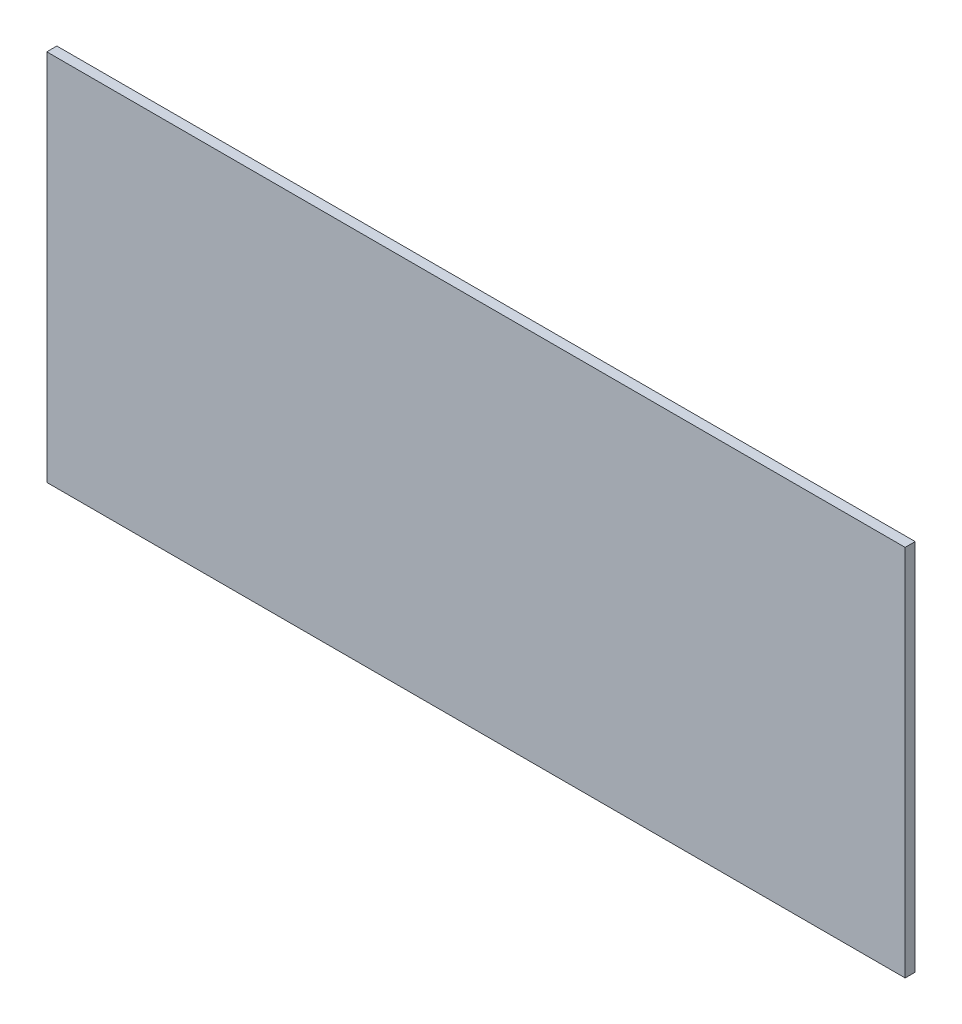
SolidWorks part; units mm, degrees
ref_plane "Front Plane" through (0, 0, 0) normal (0, 0, 1) x (1, 0, 0)
ref_plane "Top Plane" through (0, 0, 0) normal (0, 1, 0) x (1, 0, 0)
ref_plane "Right Plane" through (0, 0, 0) normal (1, 0, 0) x (0, 0, -1)
sketch "Sketch1" plane through (0, 0, 0) normal (0, 0, 1) x (1, 0, 0)
  line L1 (-104.1671, 3) -> (151.894, 3)
  line L2 (-104.1671, 3) -> (-104.1671, -108.25)
  line L3 (-104.1671, -108.25) -> (151.894, -108.25)
  line L4 (151.894, 3) -> (151.894, -108.25)
extrude "Boss-Extrude1" add sketch "Sketch1" along normal blind 3 contours L1 L4 L3 L2
